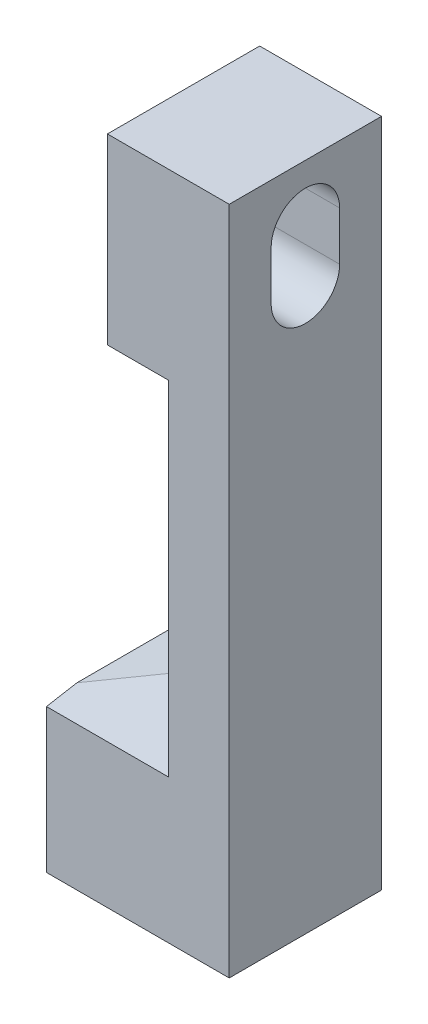
SolidWorks part; units mm, degrees
ref_plane "Front Plane" through (0, 0, 0) normal (0, 0, 1) x (1, 0, 0)
ref_plane "Top Plane" through (0, 0, 0) normal (0, 1, 0) x (1, 0, 0)
ref_plane "Right Plane" through (0, 0, 0) normal (1, 0, 0) x (0, 0, -1)
sketch "Sketch1" plane through (0, 0, 0) normal (1, 0, 0) x (0, 0, -1)
  line L1 (-7.9375, 34.925) -> (7.9375, 34.925)
  line L2 (-7.9375, 34.925) -> (-7.9375, -34.925)
  line L3 (-7.9375, -34.925) -> (7.9375, -34.925)
  line L4 (7.9375, 34.925) -> (7.9375, -34.925)
  line L5 (-7.9375, 34.925) -> (7.9375, -34.925) construction
  line L6 (-7.9375, -34.925) -> (7.9375, 34.925) construction
  point P0 (0, 0)
  dimension "D1" = 69.85
  dimension "D2" = 15.875
extrude "Boss-Extrude1" add sketch "Sketch1" along normal blind 6.35
sketch "Sketch2" plane through (0, 0, 0) normal (-1, 0, 0) x (0, 0, 1)
  line L0 (-7.9375, -34.925) -> (-7.9375, 34.925) construction
  line L1 (7.9375, 34.925) -> (-7.9375, 34.925)
  line L2 (7.9375, 34.925) -> (7.9375, 15.875)
  line L4 (-7.9375, 34.925) -> (-7.9375, 18.6742)
  line L5 (-7.9375, 18.6742) -> (7.9375, 15.875)
  line L6 (-7.9375, -34.925) -> (-7.9375, 34.925) construction
  dimension "D1" = 80
  dimension "D2" = 19.05
extrude "Boss-Extrude2" add sketch "Sketch2" along normal blind 6.35
sketch "Sketch3" plane through (0, 0, 0) normal (-1, 0, 0) x (0, 0, 1)
  line L0 (-7.9375, -34.925) -> (-7.9375, 18.6742) construction
  line L1 (-7.9375, -17.145) -> (-7.9375, -34.925)
  line L2 (-7.9375, -34.925) -> (7.9375, -34.925)
  line L3 (7.9375, -34.925) -> (7.9375, -19.9442)
  line L4 (7.9375, 15.875) -> (7.9375, -34.925) construction
  line L5 (7.9375, -19.9442) -> (-7.9375, -17.145)
  dimension "D1" = 80
  dimension "D2" = 17.78
extrude "Boss-Extrude3" add sketch "Sketch3" along normal blind 12.7
sketch "Sketch6" plane through (0, 0, -7.9375) normal (0, 0, -1) x (-1, 0, 0)
  line L0 (0, -17.145) -> (12.7, -17.145)
  line L2 (12.7, -17.145) -> (12.7, -19.3844)
  line L3 (12.7, -19.3844) -> (0, -17.145)
  line L7 (12.7, -19.9442) -> (12.7, -17.145) construction
  dimension "D1" = 10
extrude "Cut-Extrude1" cut sketch "Sketch6" against normal through all
hole_wizard "1/4 Clearance Hole1" positions "Sketch4" profile "Sketch5" hole size "1/4" standard "ANSI Inch"
sketch "Sketch4" plane through (6.35, 0, 0) normal (1, 0, 0) x (0, 0, -1)
  line L1 (7.9375, 18.6742) -> (-7.9375, 15.875) construction
  point P0 (0, 27.5913)
  dimension "D1" = 10.16
sketch "Sketch5" plane through (6.35, 27.5913, 0) normal (0, 1, 0) x (0, 0, -1)
  line L0 (0, 0) -> (0, 19.05)
  line L1 (0, 19.05) -> (3.5712, 19.05)
  line L2 (3.5712, 19.05) -> (3.5712, 0)
  line L5 (3.5712, 0) -> (0, 0)
  line L11 (0, -6.35) -> (0, 107.95) construction
  dimension "Thru Hole Dia." = 7.1425
  dimension "Thru Hole Depth" = 19.05
sketch "Sketch7" plane through (-6.35, 0, 0) normal (-1, 0, 0) x (0, 0, 1)
  line L0 (0, 28.8417) -> (0, 23.7617) construction
  line L1 (3.5687, 28.8417) -> (3.5687, 23.7617)
  line L2 (-3.5687, 28.8417) -> (-3.5687, 23.7617)
  line L3 (-7.9375, 18.6742) -> (7.9375, 15.875) construction
  arc A0 (3.5687, 28.8417) -> (-3.5687, 28.8417) centre (0, 28.8417) ccw
  arc A1 (-3.5687, 23.7617) -> (3.5687, 23.7617) centre (0, 23.7617) ccw
  point P3 (0, 26.3017)
  dimension "D1" = 5.08
  dimension "D2" = 7.1374
  dimension "D3" = 8.89
extrude "Cut-Extrude2" cut sketch "Sketch7" against normal through all
